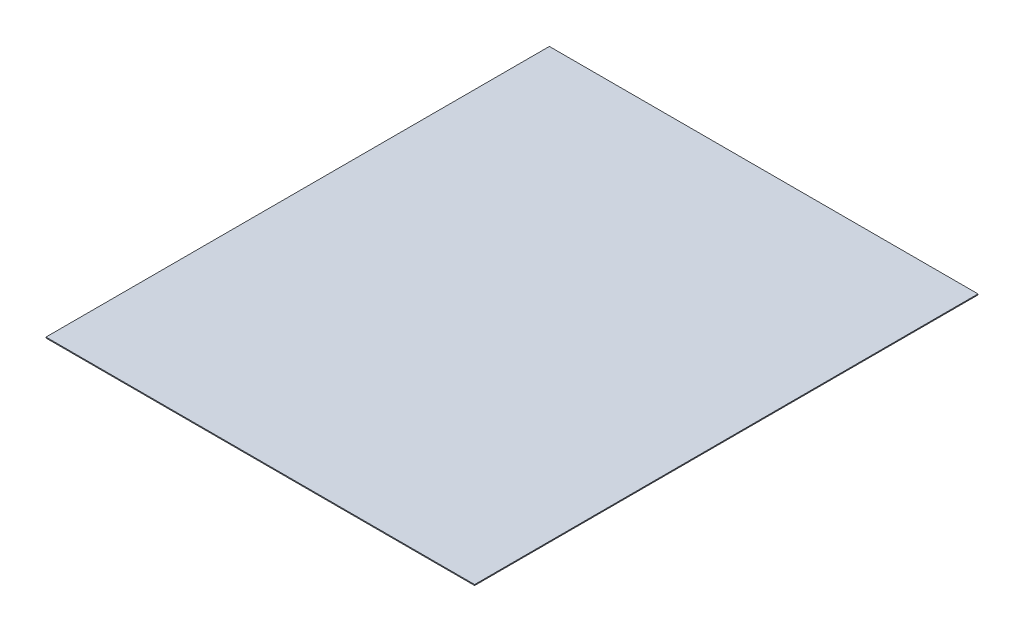
SolidWorks part; units mm, degrees
ref_plane "Front Plane" through (0, 0, 0) normal (0, 0, 1) x (1, 0, 0)
ref_plane "Top Plane" through (0, 0, 0) normal (0, 1, 0) x (1, 0, 0)
ref_plane "Right Plane" through (0, 0, 0) normal (1, 0, 0) x (0, 0, -1)
other "Configuration Table"
sketch "Sketch1" plane through (0, 0, 0) normal (0, 0, 1) x (1, 0, 0)
  line L1 (1.5, 120) -> (698.5, 120)
  line L2 (1.5, 120) -> (1.5, 121.5)
  line L3 (1.5, 121.5) -> (698.5, 121.5)
  line L4 (698.5, 120) -> (698.5, 121.5)
extrude "PACK_dis_alt_1" add sketch "Sketch1" against normal blind 818.5 separate body
